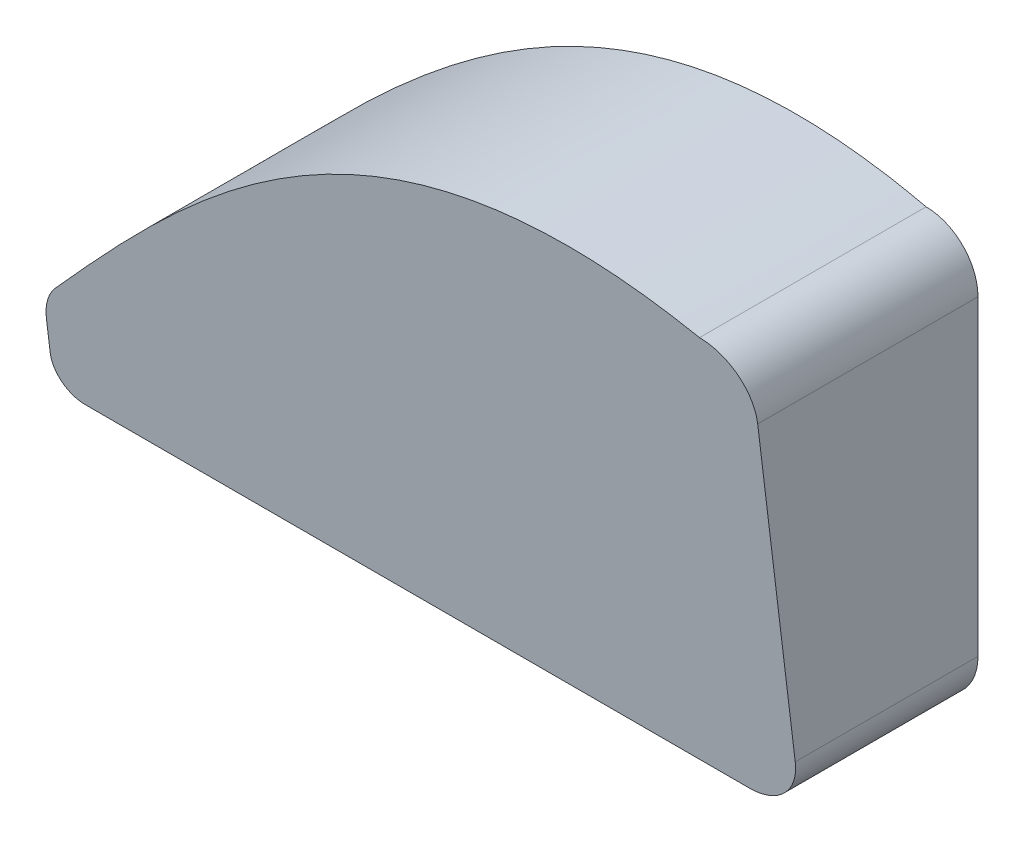
SolidWorks part; units mm, degrees
ref_plane "Front Plane" through (0, 0, 0) normal (0, 0, 1) x (1, 0, 0)
ref_plane "Top Plane" through (0, 0, 0) normal (0, 1, 0) x (1, 0, 0)
ref_plane "Right Plane" through (0, 0, 0) normal (1, 0, 0) x (0, 0, -1)
sketch "Sketch1" plane through (0, 0, 0) normal (0, 0, 1) x (1, 0, 0)
  line L2 (54.303, 17.599) -> (54.303, -12.3967)
  line L3 (49.303, -17.3967) -> (-14.6956, -17.3967)
  line L4 (-17.6956, -11.3067) -> (-17.6956, -14.3967)
  arc A0 (54.303, 17.599) -> (49.303, 22.599) centre (49.303, 17.599) ccw
  arc A1 (49.303, -17.3967) -> (54.303, -12.3967) centre (49.303, -12.3967) ccw
  arc A2 (-17.6956, -11.3067) -> (-16.3915, -7.9392) centre (-12.6956, -11.3067) cw
  arc A3 (-14.6956, -17.3967) -> (-17.6956, -14.3967) centre (-14.6956, -14.3967) cw
  spline S0 degree 3 poles (-16.3915, -7.9392) (-0.1359, 9.9015) (18.6969, 29.7257) (49.303, 22.599) knots 0.0263 0.0263 0.0263 0.0263 1 1 1 1
  point P1 (-17.6956, -17.3967)
  point P6 (-17.6956, -9.3967)
  point P10 (-15.897, -7.3967)
  point P13 (54.303, 22.599)
  point P20 (-17.6956, -17.3967)
  dimension "D4" = 5
  dimension "D7" = 5
  dimension "D2" = 5
  dimension "D1" = 3
  dimension "D3" = 5
  dimension "D5" = 8
  dimension "D6" = 10
extrude "Boss-Extrude1" add sketch "Sketch1" along normal blind 22 contours A0 S0 A2 L4 A3 L3 A1 L2
sketch "Sketch3" plane through (0, 0, 0) normal (1, 0, 0) x (0, 0, -1)
  line L0 (-22, 24.0876) -> (-17, -17.3967)
  line L1 (-22, -17.3967) -> (0, -17.3967) construction
  point P5 (0, 24.0876)
  point P6 (0, 24.0876)
  point P8 (-22, 24.0876)
  dimension "D1" = 5
extrude "Cut-Extrude3" cut sketch "Sketch3" against normal through all and the other way through all flip side to cut
